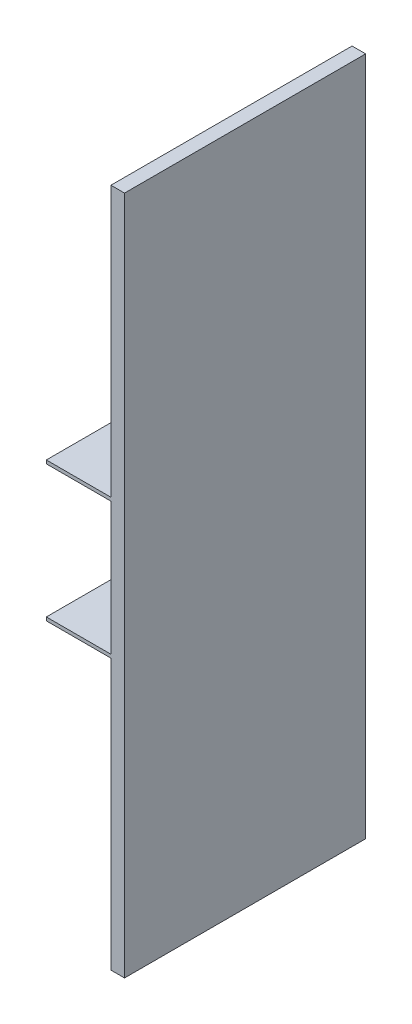
SolidWorks part; units mm, degrees
ref_plane "Front Plane" through (0, 0, 0) normal (0, 0, 1) x (1, 0, 0)
ref_plane "Top Plane" through (0, 0, 0) normal (0, 1, 0) x (1, 0, 0)
ref_plane "Right Plane" through (0, 0, 0) normal (1, 0, 0) x (0, 0, -1)
sketch "Sketch1" plane through (0, 0, 0) normal (0, 1, 0) x (1, 0, 0)
  line L1 (-11.5, 35.475) -> (11.5, 35.475)
  line L2 (-11.5, 35.475) -> (-11.5, -35.475)
  line L3 (-11.5, -35.475) -> (11.5, -35.475)
  line L4 (11.5, 35.475) -> (11.5, -35.475)
  line L5 (-11.5, 35.475) -> (11.5, -35.475) construction
  line L6 (-11.5, -35.475) -> (11.5, 35.475) construction
  point P0 (0, 0)
  dimension "D1" = 70.95
  dimension "D2" = 23
extrude "Boss-Extrude1" add sketch "Sketch1" along normal blind 200
sketch "Sketch2" plane through (0, 200, 0) normal (0, 1, 0) x (1, 0, 0)
  line L0 (-11.5, -35.475) -> (11.5, -35.475) construction
  line L1 (-11.5, 35.475) -> (7.5, 35.475)
  line L2 (-11.5, 35.475) -> (-11.5, -35.475)
  line L3 (-11.5, -35.475) -> (7.5, -35.475)
  line L4 (7.5, 35.475) -> (7.5, -35.475)
  line L5 (11.5, -35.475) -> (11.5, 35.475) construction
  dimension "D1" = 4
extrude "Cut-Extrude1" cut sketch "Sketch2" against normal through all
sketch "Sketch3" plane through (7.5, 0, 0) normal (-1, 0, 0) x (0, 0, 1)
  line L0 (-35.475, 0) -> (-35.475, 200) construction
  line L1 (-35.475, 79.5) -> (35.475, 79.5)
  line L2 (-35.475, 79.5) -> (-35.475, 80.5)
  line L3 (-35.475, 80.5) -> (35.475, 80.5)
  line L4 (35.475, 79.5) -> (35.475, 80.5)
  line L5 (35.475, 0) -> (35.475, 200) construction
  line L6 (35.475, 0) -> (-35.475, 0) construction
  line L7 (35.475, 200) -> (-35.475, 200) construction
  line L8 (-35.475, 120.5) -> (35.475, 120.5)
  line L9 (-35.475, 120.5) -> (-35.475, 119.5)
  line L10 (-35.475, 119.5) -> (35.475, 119.5)
  line L11 (35.475, 120.5) -> (35.475, 119.5)
  dimension "D1" = 1
  dimension "D2" = 79.5
  dimension "D3" = 1
  dimension "D4" = 79.5
extrude "Boss-Extrude2" add sketch "Sketch3" along normal blind 19
